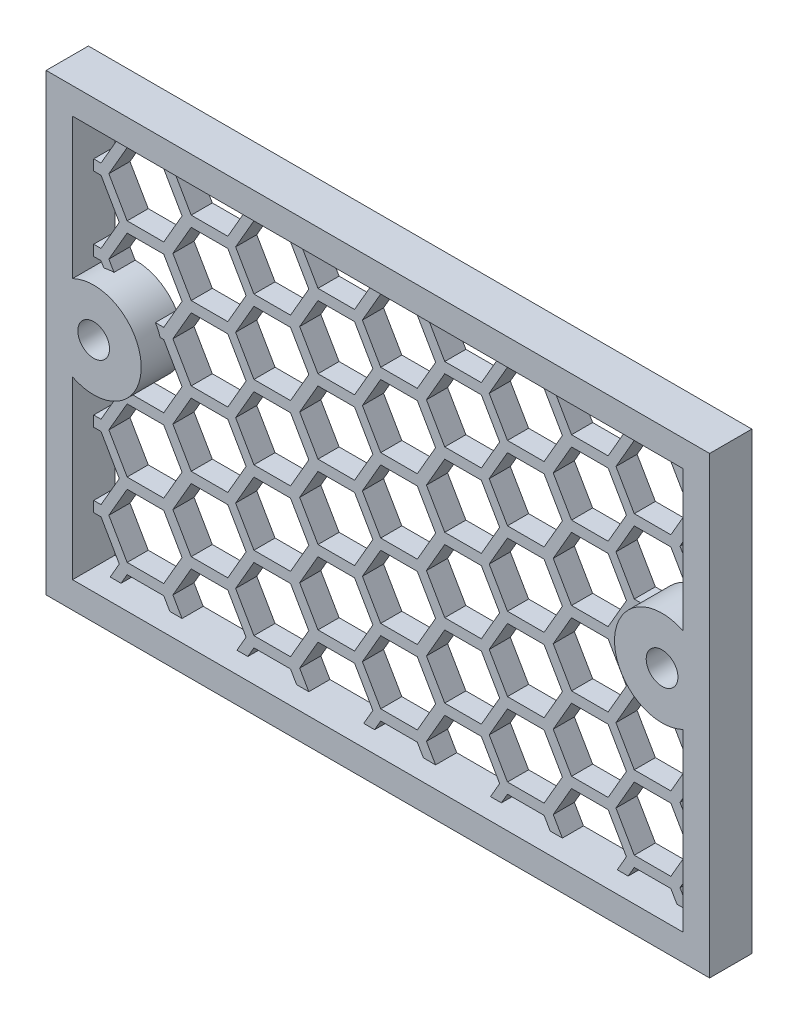
SolidWorks part; units mm, degrees
ref_plane "Plano frontal" through (0, 0, 0) normal (0, 0, 1) x (1, 0, 0)
ref_plane "Plano superior" through (0, 0, 0) normal (0, 1, 0) x (1, 0, 0)
ref_plane "Plano direito" through (0, 0, 0) normal (1, 0, 0) x (0, 0, -1)
sketch "Esboço1" plane through (0, 0, 0) normal (0, 0, 1) x (1, 0, 0)
  line L0 (-45.5019, 12.056) -> (17.2981, 12.056)
  line L1 (-45.5019, 12.056) -> (-45.5019, -30.9425)
  line L2 (-45.5019, -30.9425) -> (17.2981, -30.9425)
  line L3 (17.2981, 12.056) -> (17.2981, -30.9425)
  line L4 (-21.7718, -2.9433) -> (-23.5039, -5.9433)
  line L5 (-23.5039, -5.9433) -> (-21.7718, -8.9433)
  line L6 (-43.0019, 9.556) -> (-43.0019, 5.0567)
  line L7 (-21.7718, -8.9433) -> (-18.3077, -8.9433)
  line L8 (14.7981, 9.556) -> (14.7981, 5.0567)
  line L9 (-18.3077, -8.9433) -> (-16.5757, -5.9433)
  line L10 (-16.5757, -5.9433) -> (-18.3077, -2.9433)
  line L11 (-18.3077, -2.9433) -> (-21.7718, -2.9433)
  line L12 (-10.6378, -9.4433) -> (-12.3699, -6.4433)
  line L13 (-12.3699, -6.4433) -> (-15.834, -6.4433)
  line L14 (-15.834, -6.4433) -> (-17.566, -9.4433)
  line L15 (-17.566, -9.4433) -> (-15.834, -12.4433)
  line L16 (-15.834, -12.4433) -> (-12.3699, -12.4433)
  line L17 (-12.3699, -12.4433) -> (-10.6378, -9.4433)
  line L18 (-15.834, 0.5567) -> (-17.566, -2.4433)
  line L19 (-17.566, -2.4433) -> (-15.834, -5.4433)
  line L20 (-15.834, -5.4433) -> (-12.3699, -5.4433)
  line L21 (-12.3699, -5.4433) -> (-10.6378, -2.4433)
  line L22 (-10.6378, -2.4433) -> (-12.3699, 0.5567)
  line L23 (-12.3699, 0.5567) -> (-15.834, 0.5567)
  line L24 (-15.834, 7.5567) -> (-17.566, 4.5567)
  line L25 (-17.566, 4.5567) -> (-15.834, 1.5567)
  line L26 (-15.834, 1.5567) -> (-12.3699, 1.5567)
  line L27 (-12.3699, 1.5567) -> (-10.6378, 4.5567)
  line L28 (-10.6378, 4.5567) -> (-12.3699, 7.5567)
  line L29 (-12.3699, 7.5567) -> (-15.834, 7.5567)
  line L30 (14.7981, -11.8206) -> (14.7981, -15.9433)
  line L31 (-16.4109, 9.556) -> (-15.834, 8.5567)
  line L32 (-15.834, 8.5567) -> (-12.3699, 8.5567)
  line L33 (-12.3699, 8.5567) -> (-11.793, 9.556)
  line L34 (14.7981, 4.0567) -> (14.2282, 4.0567)
  line L35 (14.7981, -2.9433) -> (14.2282, -2.9433)
  line L36 (-15.834, -13.4433) -> (-17.566, -16.4433)
  line L37 (-17.566, -16.4433) -> (-15.834, -19.4433)
  line L38 (-15.834, -19.4433) -> (-12.3699, -19.4433)
  line L39 (-12.3699, -19.4433) -> (-10.6378, -16.4433)
  line L40 (-10.6378, -16.4433) -> (-12.3699, -13.4433)
  line L41 (-12.3699, -13.4433) -> (-15.834, -13.4433)
  line L42 (-15.834, -20.4433) -> (-17.566, -23.4433)
  line L43 (-17.566, -23.4433) -> (-15.834, -26.4433)
  line L44 (-15.834, -26.4433) -> (-12.3699, -26.4433)
  line L45 (-12.3699, -26.4433) -> (-10.6378, -23.4433)
  line L46 (-10.6378, -23.4433) -> (-12.3699, -20.4433)
  line L47 (-12.3699, -20.4433) -> (-15.834, -20.4433)
  line L48 (-15.834, -27.4433) -> (-16.4109, -28.4425)
  line L49 (-43.0019, 5.0567) -> (-42.3077, 5.0567)
  line L50 (-43.0019, -22.9433) -> (-42.3077, -22.9433)
  line L51 (-43.0019, -2.9433) -> (-43.0019, -3.7583)
  line L52 (-11.793, -28.4425) -> (-12.3699, -27.4433)
  line L53 (-12.3699, -27.4433) -> (-15.834, -27.4433)
  line L54 (-9.7718, -2.9433) -> (-11.5039, -5.9433)
  line L55 (-11.5039, -5.9433) -> (-9.7718, -8.9433)
  line L56 (-9.7718, -8.9433) -> (-6.3077, -8.9433)
  line L57 (-6.3077, -8.9433) -> (-4.5757, -5.9433)
  line L58 (-4.5757, -5.9433) -> (-6.3077, -2.9433)
  line L59 (-6.3077, -2.9433) -> (-9.7718, -2.9433)
  line L60 (-11.5039, 1.0567) -> (-9.7718, -1.9433)
  line L61 (-9.7718, -1.9433) -> (-6.3077, -1.9433)
  line L62 (-6.3077, -1.9433) -> (-4.5757, 1.0567)
  line L63 (-4.5757, 1.0567) -> (-6.3077, 4.0567)
  line L64 (-9.7718, 4.0567) -> (-11.5039, 1.0567)
  line L65 (-6.3077, 4.0567) -> (-9.7718, 4.0567)
  line L66 (-11.5039, 8.0567) -> (-9.7718, 5.0567)
  line L67 (-9.7718, 5.0567) -> (-6.3077, 5.0567)
  line L68 (-6.3077, 5.0567) -> (-4.5757, 8.0567)
  line L69 (-4.5757, 8.0567) -> (-5.4412, 9.556)
  line L70 (-10.6383, 9.556) -> (-11.5039, 8.0567)
  line L71 (-43.0019, -15.9433) -> (-42.3077, -15.9433)
  line L72 (-11.5039, -12.9433) -> (-9.7718, -15.9433)
  line L73 (-9.7718, -15.9433) -> (-6.3077, -15.9433)
  line L74 (-6.3077, -15.9433) -> (-4.5757, -12.9433)
  line L75 (-4.5757, -12.9433) -> (-6.3077, -9.9433)
  line L76 (-9.7718, -9.9433) -> (-11.5039, -12.9433)
  line L77 (-6.3077, -9.9433) -> (-9.7718, -9.9433)
  line L78 (-11.5039, -19.9433) -> (-9.7718, -22.9433)
  line L79 (-9.7718, -22.9433) -> (-6.3077, -22.9433)
  line L80 (-6.3077, -22.9433) -> (-4.5757, -19.9433)
  line L81 (-4.5757, -19.9433) -> (-6.3077, -16.9433)
  line L82 (-9.7718, -16.9433) -> (-11.5039, -19.9433)
  line L83 (-6.3077, -16.9433) -> (-9.7718, -16.9433)
  line L84 (-11.5039, -26.9433) -> (-10.6383, -28.4425)
  line L85 (-43.0019, -11.8206) -> (-43.0019, -15.9433)
  line L86 (-5.4412, -28.4425) -> (-4.5757, -26.9433)
  line L87 (-4.5757, -26.9433) -> (-6.3077, -23.9433)
  line L88 (-9.7718, -23.9433) -> (-11.5039, -26.9433)
  line L89 (-6.3077, -23.9433) -> (-9.7718, -23.9433)
  line L90 (-43.0019, -28.4425) -> (14.7981, -28.4425) construction
  line L91 (-43.0019, 9.556) -> (14.7981, 9.556) construction
  line L92 (-23.5039, 1.0567) -> (-21.7718, -1.9433)
  line L93 (-21.7718, -1.9433) -> (-18.3077, -1.9433)
  line L94 (-18.3077, -1.9433) -> (-16.5757, 1.0567)
  line L95 (-16.5757, 1.0567) -> (-18.3077, 4.0567)
  line L96 (-21.7718, 4.0567) -> (-23.5039, 1.0567)
  line L97 (-18.3077, 4.0567) -> (-21.7718, 4.0567)
  line L98 (-23.5039, 8.0567) -> (-21.7718, 5.0567)
  line L99 (-21.7718, 5.0567) -> (-18.3077, 5.0567)
  line L100 (-18.3077, 5.0567) -> (-16.5757, 8.0567)
  line L101 (-16.5757, 8.0567) -> (-17.4412, 9.556)
  line L102 (-22.6383, 9.556) -> (-23.5039, 8.0567)
  line L103 (14.7981, 9.556) -> (14.7981, -28.4425) construction
  line L104 (-23.5039, -12.9433) -> (-21.7718, -15.9433)
  line L105 (-21.7718, -15.9433) -> (-18.3077, -15.9433)
  line L106 (-18.3077, -15.9433) -> (-16.5757, -12.9433)
  line L107 (-16.5757, -12.9433) -> (-18.3077, -9.9433)
  line L108 (-21.7718, -9.9433) -> (-23.5039, -12.9433)
  line L109 (-18.3077, -9.9433) -> (-21.7718, -9.9433)
  line L110 (-23.5039, -19.9433) -> (-21.7718, -22.9433)
  line L111 (-21.7718, -22.9433) -> (-18.3077, -22.9433)
  line L112 (-18.3077, -22.9433) -> (-16.5757, -19.9433)
  line L113 (-16.5757, -19.9433) -> (-18.3077, -16.9433)
  line L114 (-21.7718, -16.9433) -> (-23.5039, -19.9433)
  line L115 (-18.3077, -16.9433) -> (-21.7718, -16.9433)
  line L116 (-23.5039, -26.9433) -> (-22.6383, -28.4425)
  line L117 (-43.0019, -1.9433) -> (-42.3077, -1.9433)
  line L118 (-17.4412, -28.4425) -> (-16.5757, -26.9433)
  line L119 (-16.5757, -26.9433) -> (-18.3077, -23.9433)
  line L120 (-21.7718, -23.9433) -> (-23.5039, -26.9433)
  line L121 (-18.3077, -23.9433) -> (-21.7718, -23.9433)
  line L122 (-33.7718, -2.9433) -> (-35.5039, -5.9433)
  line L123 (-35.5039, -5.9433) -> (-33.7718, -8.9433)
  line L124 (-33.7718, -8.9433) -> (-30.3077, -8.9433)
  line L125 (-30.3077, -8.9433) -> (-28.5757, -5.9433)
  line L126 (-28.5757, -5.9433) -> (-30.3077, -2.9433)
  line L127 (-30.3077, -2.9433) -> (-33.7718, -2.9433)
  line L128 (-35.5039, 1.0567) -> (-33.7718, -1.9433)
  line L129 (-33.7718, -1.9433) -> (-30.3077, -1.9433)
  line L130 (-30.3077, -1.9433) -> (-28.5757, 1.0567)
  line L131 (-28.5757, 1.0567) -> (-30.3077, 4.0567)
  line L132 (-33.7718, 4.0567) -> (-35.5039, 1.0567)
  line L133 (-30.3077, 4.0567) -> (-33.7718, 4.0567)
  line L134 (-35.5039, 8.0567) -> (-33.7718, 5.0567)
  line L135 (-33.7718, 5.0567) -> (-30.3077, 5.0567)
  line L136 (-30.3077, 5.0567) -> (-28.5757, 8.0567)
  line L137 (-28.5757, 8.0567) -> (-29.4412, 9.556)
  line L138 (-34.6383, 9.556) -> (-35.5039, 8.0567)
  line L139 (8.5042, -6.4433) -> (8.166, -6.4433)
  line L140 (-35.5039, -12.9433) -> (-33.7718, -15.9433)
  line L141 (-33.7718, -15.9433) -> (-30.3077, -15.9433)
  line L142 (-30.3077, -15.9433) -> (-28.5757, -12.9433)
  line L143 (-28.5757, -12.9433) -> (-30.3077, -9.9433)
  line L144 (-33.7718, -9.9433) -> (-35.5039, -12.9433)
  line L145 (-30.3077, -9.9433) -> (-33.7718, -9.9433)
  line L146 (-35.5039, -19.9433) -> (-33.7718, -22.9433)
  line L147 (-33.7718, -22.9433) -> (-30.3077, -22.9433)
  line L148 (-30.3077, -22.9433) -> (-28.5757, -19.9433)
  line L149 (-28.5757, -19.9433) -> (-30.3077, -16.9433)
  line L150 (-33.7718, -16.9433) -> (-35.5039, -19.9433)
  line L151 (-30.3077, -16.9433) -> (-33.7718, -16.9433)
  line L152 (-35.5039, -26.9433) -> (-34.6383, -28.4425)
  line L153 (-43.0019, 9.556) -> (-43.0019, -28.4425) construction
  line L154 (-29.4412, -28.4425) -> (-28.5757, -26.9433)
  line L155 (-28.5757, -26.9433) -> (-30.3077, -23.9433)
  line L156 (-33.7718, -23.9433) -> (-35.5039, -26.9433)
  line L157 (-30.3077, -23.9433) -> (-33.7718, -23.9433)
  line L158 (14.7981, -16.9433) -> (14.2282, -16.9433)
  line L159 (14.7981, -23.9433) -> (14.2282, -23.9433)
  line L160 (-39.9894, -12.1741) -> (-39.834, -12.4433)
  line L161 (-43.0019, -16.9433) -> (-43.0019, -22.9433)
  line L162 (-42.038, -3.4104) -> (-42.3077, -2.9433)
  line L163 (-42.3077, -2.9433) -> (-43.0019, -2.9433)
  line L164 (-43.0019, -23.9433) -> (-43.0019, -28.4425)
  line L165 (-40.4109, -28.4425) -> (-35.793, -28.4425)
  line L166 (-42.3077, -1.9433) -> (-40.5757, 1.0567)
  line L167 (-40.5757, 1.0567) -> (-42.3077, 4.0567)
  line L168 (-34.6383, -28.4425) -> (-29.4412, -28.4425)
  line L169 (-42.3077, 4.0567) -> (-43.0019, 4.0567)
  line L170 (-28.4109, -28.4425) -> (-23.793, -28.4425)
  line L171 (-22.6383, -28.4425) -> (-17.4412, -28.4425)
  line L172 (-42.3077, 5.0567) -> (-40.5757, 8.0567)
  line L173 (-40.5757, 8.0567) -> (-41.4412, 9.556)
  line L174 (-16.4109, -28.4425) -> (-11.793, -28.4425)
  line L175 (-10.6383, -28.4425) -> (-5.4412, -28.4425)
  line L176 (-4.4109, -28.4425) -> (0.207, -28.4425)
  line L177 (1.3617, -28.4425) -> (6.5588, -28.4425)
  line L178 (-42.3077, -15.9433) -> (-40.5757, -12.9433)
  line L179 (-40.5757, -12.9433) -> (-40.9533, -12.2892)
  line L180 (7.5891, -28.4425) -> (12.207, -28.4425)
  line L181 (13.3617, -28.4425) -> (14.7981, -28.4425)
  line L182 (14.7981, -23.9433) -> (14.7981, -28.4425)
  line L183 (14.7981, -16.9433) -> (14.7981, -22.9433)
  line L184 (-42.3077, -22.9433) -> (-40.5757, -19.9433)
  line L185 (-40.5757, -19.9433) -> (-42.3077, -16.9433)
  line L186 (14.7981, -2.9433) -> (14.7981, -3.7583)
  line L187 (-42.3077, -16.9433) -> (-43.0019, -16.9433)
  line L188 (14.7981, 4.0567) -> (14.7981, -1.9433)
  line L189 (13.3617, 9.556) -> (14.7981, 9.556)
  line L190 (-41.4412, -28.4425) -> (-40.5757, -26.9433)
  line L191 (-40.5757, -26.9433) -> (-42.3077, -23.9433)
  line L192 (7.5891, 9.556) -> (12.207, 9.556)
  line L193 (-42.3077, -23.9433) -> (-43.0019, -23.9433)
  line L194 (2.2282, -2.9433) -> (0.4961, -5.9433)
  line L195 (0.4961, -5.9433) -> (2.2282, -8.9433)
  line L196 (2.2282, -8.9433) -> (5.6923, -8.9433)
  line L197 (5.6923, -8.9433) -> (7.4243, -5.9433)
  line L198 (7.4243, -5.9433) -> (5.6923, -2.9433)
  line L199 (5.6923, -2.9433) -> (2.2282, -2.9433)
  line L200 (0.4961, 1.0567) -> (2.2282, -1.9433)
  line L201 (2.2282, -1.9433) -> (5.6923, -1.9433)
  line L202 (5.6923, -1.9433) -> (7.4243, 1.0567)
  line L203 (7.4243, 1.0567) -> (5.6923, 4.0567)
  line L204 (2.2282, 4.0567) -> (0.4961, 1.0567)
  line L205 (5.6923, 4.0567) -> (2.2282, 4.0567)
  line L206 (0.4961, 8.0567) -> (2.2282, 5.0567)
  line L207 (2.2282, 5.0567) -> (5.6923, 5.0567)
  line L208 (5.6923, 5.0567) -> (7.4243, 8.0567)
  line L209 (7.4243, 8.0567) -> (6.5588, 9.556)
  line L210 (1.3617, 9.556) -> (0.4961, 8.0567)
  line L211 (1.3617, 9.556) -> (6.5588, 9.556)
  line L212 (0.4961, -12.9433) -> (2.2282, -15.9433)
  line L213 (2.2282, -15.9433) -> (5.6923, -15.9433)
  line L214 (5.6923, -15.9433) -> (7.4243, -12.9433)
  line L215 (7.4243, -12.9433) -> (5.6923, -9.9433)
  line L216 (2.2282, -9.9433) -> (0.4961, -12.9433)
  line L217 (5.6923, -9.9433) -> (2.2282, -9.9433)
  line L218 (0.4961, -19.9433) -> (2.2282, -22.9433)
  line L219 (2.2282, -22.9433) -> (5.6923, -22.9433)
  line L220 (5.6923, -22.9433) -> (7.4243, -19.9433)
  line L221 (7.4243, -19.9433) -> (5.6923, -16.9433)
  line L222 (2.2282, -16.9433) -> (0.4961, -19.9433)
  line L223 (5.6923, -16.9433) -> (2.2282, -16.9433)
  line L224 (0.4961, -26.9433) -> (1.3617, -28.4425)
  line L225 (-4.4109, 9.556) -> (0.207, 9.556)
  line L226 (6.5588, -28.4425) -> (7.4243, -26.9433)
  line L227 (7.4243, -26.9433) -> (5.6923, -23.9433)
  line L228 (2.2282, -23.9433) -> (0.4961, -26.9433)
  line L229 (5.6923, -23.9433) -> (2.2282, -23.9433)
  line L230 (14.2282, -2.9433) -> (13.9428, -3.4375)
  line L231 (-10.6383, 9.556) -> (-5.4412, 9.556)
  line L232 (-16.4109, 9.556) -> (-11.793, 9.556)
  line L233 (-22.6383, 9.556) -> (-17.4412, 9.556)
  line L234 (-28.4109, 9.556) -> (-23.793, 9.556)
  line L235 (-34.6383, 9.556) -> (-29.4412, 9.556)
  line L236 (12.4961, 1.0567) -> (14.2282, -1.9433)
  line L237 (14.2282, -1.9433) -> (14.7981, -1.9433)
  line L238 (-40.4109, 9.556) -> (-35.793, 9.556)
  line L239 (-43.0019, 4.0567) -> (-43.0019, -1.9433)
  line L240 (14.2282, 4.0567) -> (12.4961, 1.0567)
  line L242 (12.4961, 8.0567) -> (14.2282, 5.0567)
  line L243 (14.2282, 5.0567) -> (14.7981, 5.0567)
  line L246 (13.3617, 9.556) -> (12.4961, 8.0567)
  line L248 (12.4961, -12.9433) -> (14.2282, -15.9433)
  line L249 (14.2282, -15.9433) -> (14.7981, -15.9433)
  line L252 (12.874, -12.2888) -> (12.4961, -12.9433)
  line L254 (12.4961, -19.9433) -> (14.2282, -22.9433)
  line L255 (14.2282, -22.9433) -> (14.7981, -22.9433)
  line L258 (14.2282, -16.9433) -> (12.4961, -19.9433)
  line L260 (12.4961, -26.9433) -> (13.3617, -28.4425)
  line L264 (14.2282, -23.9433) -> (12.4961, -26.9433)
  line L266 (1.3622, -9.4433) -> (-0.3699, -6.4433)
  line L267 (-0.3699, -6.4433) -> (-3.834, -6.4433)
  line L268 (-3.834, -6.4433) -> (-5.566, -9.4433)
  line L269 (-5.566, -9.4433) -> (-3.834, -12.4433)
  line L270 (-3.834, -12.4433) -> (-0.3699, -12.4433)
  line L271 (-0.3699, -12.4433) -> (1.3622, -9.4433)
  line L272 (-3.834, 0.5567) -> (-5.566, -2.4433)
  line L273 (-5.566, -2.4433) -> (-3.834, -5.4433)
  line L274 (-3.834, -5.4433) -> (-0.3699, -5.4433)
  line L275 (-0.3699, -5.4433) -> (1.3622, -2.4433)
  line L276 (1.3622, -2.4433) -> (-0.3699, 0.5567)
  line L277 (-0.3699, 0.5567) -> (-3.834, 0.5567)
  line L278 (-3.834, 7.5567) -> (-5.566, 4.5567)
  line L279 (-5.566, 4.5567) -> (-3.834, 1.5567)
  line L280 (-3.834, 1.5567) -> (-0.3699, 1.5567)
  line L281 (-0.3699, 1.5567) -> (1.3622, 4.5567)
  line L282 (1.3622, 4.5567) -> (-0.3699, 7.5567)
  line L283 (-0.3699, 7.5567) -> (-3.834, 7.5567)
  line L284 (-4.4109, 9.556) -> (-3.834, 8.5567)
  line L285 (-3.834, 8.5567) -> (-0.3699, 8.5567)
  line L286 (-0.3699, 8.5567) -> (0.207, 9.556)
  line L287 (-3.834, -13.4433) -> (-5.566, -16.4433)
  line L288 (-5.566, -16.4433) -> (-3.834, -19.4433)
  line L289 (-3.834, -19.4433) -> (-0.3699, -19.4433)
  line L290 (-0.3699, -19.4433) -> (1.3622, -16.4433)
  line L291 (1.3622, -16.4433) -> (-0.3699, -13.4433)
  line L292 (-0.3699, -13.4433) -> (-3.834, -13.4433)
  line L293 (-3.834, -20.4433) -> (-5.566, -23.4433)
  line L294 (-5.566, -23.4433) -> (-3.834, -26.4433)
  line L295 (-3.834, -26.4433) -> (-0.3699, -26.4433)
  line L296 (-0.3699, -26.4433) -> (1.3622, -23.4433)
  line L297 (1.3622, -23.4433) -> (-0.3699, -20.4433)
  line L298 (-0.3699, -20.4433) -> (-3.834, -20.4433)
  line L299 (-3.834, -27.4433) -> (-4.4109, -28.4425)
  line L300 (0.207, -28.4425) -> (-0.3699, -27.4433)
  line L301 (-0.3699, -27.4433) -> (-3.834, -27.4433)
  line L304 (8.166, -6.4433) -> (6.434, -9.4433)
  line L305 (6.434, -9.4433) -> (8.166, -12.4433)
  line L306 (8.166, -12.4433) -> (11.6301, -12.4433)
  line L307 (11.6301, -12.4433) -> (11.7855, -12.1741)
  line L308 (8.166, 0.5567) -> (6.434, -2.4433)
  line L309 (6.434, -2.4433) -> (8.166, -5.4433)
  line L310 (8.166, -5.4433) -> (8.9581, -5.4433)
  line L311 (12.8732, -3.2901) -> (13.3622, -2.4433)
  line L312 (13.3622, -2.4433) -> (11.6301, 0.5567)
  line L313 (11.6301, 0.5567) -> (8.166, 0.5567)
  line L314 (8.166, 7.5567) -> (6.434, 4.5567)
  line L315 (6.434, 4.5567) -> (8.166, 1.5567)
  line L316 (8.166, 1.5567) -> (11.6301, 1.5567)
  line L317 (11.6301, 1.5567) -> (13.3622, 4.5567)
  line L318 (13.3622, 4.5567) -> (11.6301, 7.5567)
  line L319 (11.6301, 7.5567) -> (8.166, 7.5567)
  line L320 (7.5891, 9.556) -> (8.166, 8.5567)
  line L321 (8.166, 8.5567) -> (11.6301, 8.5567)
  line L322 (11.6301, 8.5567) -> (12.207, 9.556)
  line L323 (8.166, -13.4433) -> (6.434, -16.4433)
  line L324 (6.434, -16.4433) -> (8.166, -19.4433)
  line L325 (8.166, -19.4433) -> (11.6301, -19.4433)
  line L326 (11.6301, -19.4433) -> (13.3622, -16.4433)
  line L327 (13.3622, -16.4433) -> (11.6301, -13.4433)
  line L328 (11.6301, -13.4433) -> (8.166, -13.4433)
  line L329 (8.166, -20.4433) -> (6.434, -23.4433)
  line L330 (6.434, -23.4433) -> (8.166, -26.4433)
  line L331 (8.166, -26.4433) -> (11.6301, -26.4433)
  line L332 (11.6301, -26.4433) -> (13.3622, -23.4433)
  line L333 (13.3622, -23.4433) -> (11.6301, -20.4433)
  line L334 (11.6301, -20.4433) -> (8.166, -20.4433)
  line L335 (8.166, -27.4433) -> (7.5891, -28.4425)
  line L336 (12.207, -28.4425) -> (11.6301, -27.4433)
  line L337 (11.6301, -27.4433) -> (8.166, -27.4433)
  line L338 (-22.6378, -9.4433) -> (-24.3699, -6.4433)
  line L339 (-24.3699, -6.4433) -> (-27.834, -6.4433)
  line L340 (-27.834, -6.4433) -> (-29.566, -9.4433)
  line L341 (-29.566, -9.4433) -> (-27.834, -12.4433)
  line L342 (-27.834, -12.4433) -> (-24.3699, -12.4433)
  line L343 (-24.3699, -12.4433) -> (-22.6378, -9.4433)
  line L344 (-27.834, 0.5567) -> (-29.566, -2.4433)
  line L345 (-29.566, -2.4433) -> (-27.834, -5.4433)
  line L346 (-27.834, -5.4433) -> (-24.3699, -5.4433)
  line L347 (-24.3699, -5.4433) -> (-22.6378, -2.4433)
  line L348 (-22.6378, -2.4433) -> (-24.3699, 0.5567)
  line L349 (-24.3699, 0.5567) -> (-27.834, 0.5567)
  line L350 (-27.834, 7.5567) -> (-29.566, 4.5567)
  line L351 (-29.566, 4.5567) -> (-27.834, 1.5567)
  line L352 (-27.834, 1.5567) -> (-24.3699, 1.5567)
  line L353 (-24.3699, 1.5567) -> (-22.6378, 4.5567)
  line L354 (-22.6378, 4.5567) -> (-24.3699, 7.5567)
  line L355 (-24.3699, 7.5567) -> (-27.834, 7.5567)
  line L356 (-28.4109, 9.556) -> (-27.834, 8.5567)
  line L357 (-27.834, 8.5567) -> (-24.3699, 8.5567)
  line L358 (-24.3699, 8.5567) -> (-23.793, 9.556)
  line L359 (-27.834, -13.4433) -> (-29.566, -16.4433)
  line L360 (-29.566, -16.4433) -> (-27.834, -19.4433)
  line L361 (-27.834, -19.4433) -> (-24.3699, -19.4433)
  line L362 (-24.3699, -19.4433) -> (-22.6378, -16.4433)
  line L363 (-22.6378, -16.4433) -> (-24.3699, -13.4433)
  line L364 (-24.3699, -13.4433) -> (-27.834, -13.4433)
  line L365 (-27.834, -20.4433) -> (-29.566, -23.4433)
  line L366 (-29.566, -23.4433) -> (-27.834, -26.4433)
  line L367 (-27.834, -26.4433) -> (-24.3699, -26.4433)
  line L368 (-24.3699, -26.4433) -> (-22.6378, -23.4433)
  line L369 (-22.6378, -23.4433) -> (-24.3699, -20.4433)
  line L370 (-24.3699, -20.4433) -> (-27.834, -20.4433)
  line L371 (-27.834, -27.4433) -> (-28.4109, -28.4425)
  line L372 (-23.793, -28.4425) -> (-24.3699, -27.4433)
  line L373 (-24.3699, -27.4433) -> (-27.834, -27.4433)
  line L374 (-34.6378, -9.4433) -> (-36.3699, -6.4433)
  line L375 (-36.3699, -6.4433) -> (-36.708, -6.4433)
  line L378 (-39.834, -12.4433) -> (-36.3699, -12.4433)
  line L379 (-36.3699, -12.4433) -> (-34.6378, -9.4433)
  line L380 (-39.834, 0.5567) -> (-41.566, -2.4433)
  line L381 (-41.566, -2.4433) -> (-41.0771, -3.2901)
  line L382 (-37.162, -5.4433) -> (-36.3699, -5.4433)
  line L383 (-36.3699, -5.4433) -> (-34.6378, -2.4433)
  line L384 (-34.6378, -2.4433) -> (-36.3699, 0.5567)
  line L385 (-36.3699, 0.5567) -> (-39.834, 0.5567)
  line L386 (-39.834, 7.5567) -> (-41.566, 4.5567)
  line L387 (-41.566, 4.5567) -> (-39.834, 1.5567)
  line L388 (-39.834, 1.5567) -> (-36.3699, 1.5567)
  line L389 (-36.3699, 1.5567) -> (-34.6378, 4.5567)
  line L390 (-34.6378, 4.5567) -> (-36.3699, 7.5567)
  line L391 (-36.3699, 7.5567) -> (-39.834, 7.5567)
  line L392 (-40.4109, 9.556) -> (-39.834, 8.5567)
  line L393 (-39.834, 8.5567) -> (-36.3699, 8.5567)
  line L394 (-36.3699, 8.5567) -> (-35.793, 9.556)
  line L395 (-39.834, -13.4433) -> (-41.566, -16.4433)
  line L396 (-41.566, -16.4433) -> (-39.834, -19.4433)
  line L397 (-39.834, -19.4433) -> (-36.3699, -19.4433)
  line L398 (-36.3699, -19.4433) -> (-34.6378, -16.4433)
  line L399 (-34.6378, -16.4433) -> (-36.3699, -13.4433)
  line L400 (-36.3699, -13.4433) -> (-39.834, -13.4433)
  line L401 (-39.834, -20.4433) -> (-41.566, -23.4433)
  line L402 (-41.566, -23.4433) -> (-39.834, -26.4433)
  line L403 (-39.834, -26.4433) -> (-36.3699, -26.4433)
  line L404 (-36.3699, -26.4433) -> (-34.6378, -23.4433)
  line L405 (-34.6378, -23.4433) -> (-36.3699, -20.4433)
  line L406 (-36.3699, -20.4433) -> (-39.834, -20.4433)
  line L407 (-39.834, -27.4433) -> (-40.4109, -28.4425)
  line L408 (-35.793, -28.4425) -> (-36.3699, -27.4433)
  line L409 (-36.3699, -27.4433) -> (-39.834, -27.4433)
  line L410 (-43.0019, 9.556) -> (-41.4412, 9.556)
  line L411 (-43.0019, -28.4425) -> (-41.4412, -28.4425)
  line L412 (-45.7718, -2.9433) -> (-47.5039, -5.9433) [skipped]
  line L413 (-47.5039, -5.9433) -> (-45.7718, -8.9433) [skipped]
  line L414 (-47.5039, 1.0567) -> (-45.7718, -1.9433) [skipped]
  line L415 (-45.7718, 4.0567) -> (-47.5039, 1.0567) [skipped]
  line L416 (-47.5039, 8.0567) -> (-45.7718, 5.0567) [skipped]
  line L417 (-45.7718, 11.0567) -> (-47.5039, 8.0567) [skipped]
  line L418 (-47.5039, -12.9433) -> (-45.7718, -15.9433) [skipped]
  line L419 (-45.7718, -9.9433) -> (-47.5039, -12.9433) [skipped]
  line L420 (-47.5039, -19.9433) -> (-45.7718, -22.9433) [skipped]
  line L421 (-45.7718, -16.9433) -> (-47.5039, -19.9433) [skipped]
  line L422 (-47.5039, -26.9433) -> (-45.7718, -29.9433) [skipped]
  line L423 (-45.7718, -23.9433) -> (-47.5039, -26.9433) [skipped]
  line L424 (17.6923, -8.9433) -> (19.4243, -5.9433) [skipped]
  line L425 (19.4243, -5.9433) -> (17.6923, -2.9433) [skipped]
  line L426 (17.6923, -1.9433) -> (19.4243, 1.0567) [skipped]
  line L427 (19.4243, 1.0567) -> (17.6923, 4.0567) [skipped]
  line L428 (17.6923, 5.0567) -> (19.4243, 8.0567) [skipped]
  line L429 (19.4243, 8.0567) -> (17.6923, 11.0567) [skipped]
  line L430 (17.6923, -15.9433) -> (19.4243, -12.9433) [skipped]
  line L431 (19.4243, -12.9433) -> (17.6923, -9.9433) [skipped]
  line L432 (17.6923, -22.9433) -> (19.4243, -19.9433) [skipped]
  line L433 (19.4243, -19.9433) -> (17.6923, -16.9433) [skipped]
  line L434 (17.6923, -29.9433) -> (19.4243, -26.9433) [skipped]
  line L435 (19.4243, -26.9433) -> (17.6923, -23.9433) [skipped]
  line L439 (-15.834, 14.5567) -> (-17.2778, 12.056) [skipped]
  line L440 (-10.9261, 12.056) -> (-12.3699, 14.5567) [skipped]
  line L441 (-12.3699, 14.5567) -> (-15.834, 14.5567) [skipped]
  line L442 (-6.3077, 11.0567) -> (-9.7718, 11.0567) [skipped]
  line L443 (17.6923, 4.0567) -> (17.2981, 4.0567) [skipped]
  line L444 (17.6923, -2.9433) -> (17.2981, -2.9433) [skipped]
  line L445 (17.6923, -9.9433) -> (17.2981, -9.9433) [skipped]
  line L446 (11.6301, -6.4433) -> (9.8981, -6.4433) [skipped]
  line L447 (14.2282, -8.9433) -> (14.7981, -8.9433) [skipped]
  line L448 (12.4961, -5.9433) -> (12.698, -6.2928) [skipped]
  line L449 (13.3622, -9.4433) -> (13.2357, -9.2242) [skipped]
  line L450 (17.6923, -16.9433) -> (17.2981, -16.9433) [skipped]
  line L451 (17.6923, -23.9433) -> (17.2981, -23.9433) [skipped]
  line L454 (-9.7718, -29.9433) -> (-6.3077, -29.9433) [skipped]
  line L455 (-17.2778, -30.9425) -> (-15.834, -33.4433) [skipped]
  line L456 (-12.3699, -33.4433) -> (-10.9261, -30.9425) [skipped]
  line L457 (-15.834, -33.4433) -> (-12.3699, -33.4433) [skipped]
  line L458 (-45.7718, -15.9433) -> (-45.5019, -15.9433) [skipped]
  line L459 (-45.7718, -22.9433) -> (-45.5019, -22.9433) [skipped]
  line L460 (-45.7718, -8.9433) -> (-45.5019, -8.9433) [skipped]
  line L461 (-45.7718, -1.9433) -> (-45.5019, -1.9433) [skipped]
  line L462 (-45.7718, 5.0567) -> (-45.5019, 5.0567) [skipped]
  line L463 (-42.3077, -9.9433) -> (-43.0019, -9.9433) [skipped]
  line L464 (-41.566, -9.4433) -> (-40.7, -10.9433) [skipped]
  line L465 (-42.1786, -8.7197) -> (-40.7847, -6.3053) [skipped]
  line L466 (-39.9782, -6.6931) -> (-40.7, -7.9433) [skipped]
  circle A0 centre (-41.0019, -7.7895) radius 1.5
  circle A1 centre (12.7981, -7.7895) radius 1.5
  arc A2 (-43.0019, -11.8206) -> (-40.9533, -12.2892) centre (-41.0019, -7.7895) ccw
  arc A3 (14.7981, -3.7583) -> (13.9428, -3.4375) centre (12.7981, -7.7895) ccw
  circle A4 centre (-14.1019, -9.4433) radius 3 construction
  circle A5 centre (-2.1019, -9.4433) radius 3 construction
  arc A6 (-42.038, -3.4104) -> (-43.0019, -3.7583) centre (-41.0019, -7.7895) ccw
  circle A7 centre (-26.1019, -9.4433) radius 3 construction
  arc A8 (-39.5744, -12.057) -> (-36.6021, -6.8451) centre (-38.1019, -9.4433) ccw construction
  arc A9 (8.3983, -6.8451) -> (11.3705, -12.057) centre (9.8981, -9.4433) ccw construction
  arc A10 (12.894, -9.2864) -> (12.4961, -7.9433) centre (9.8981, -9.4433) ccw construction
  arc A11 (-37.162, -5.4433) -> (-41.0771, -3.2901) centre (-41.0019, -7.7895) ccw
  arc A12 (-39.9894, -12.1741) -> (-36.708, -6.4433) centre (-41.0019, -7.7895) ccw
  arc A13 (12.874, -12.2888) -> (14.7981, -11.8206) centre (12.7981, -7.7895) ccw
  arc A14 (8.5042, -6.4433) -> (11.7855, -12.1741) centre (12.7981, -7.7895) ccw
  arc A15 (12.8732, -3.2901) -> (8.9581, -5.4433) centre (12.7981, -7.7895) ccw
  point P0 (-41.0019, -7.7895)
  point P1 (12.7981, -7.7895)
  point P2 (-45.5019, 12.056)
  point P3 (17.2981, 12.056)
  point P4 (17.2981, -30.9425)
  point P5 (-45.5019, -30.9425)
  point P14 (-14.1019, -9.4433)
  point P282 (-2.1019, -9.4433)
  point P323 (9.8981, -9.4433)
  point P364 (-26.1019, -9.4433)
  point P405 (-38.1019, -9.4433)
  dimension "D1" = 2.5
  dimension "D2" = 4
  dimension "D3" = 4
  dimension "D4" = 2
  dimension "D5" = 3
  dimension "D6" = 4
extrude "Ressalto-extrusão1" add sketch "Esboço1" along normal blind 2
sketch "Esboço2" plane through (0, 0, 2) normal (0, 0, 1) x (1, 0, 0)
  line L0 (-43.0019, -3.7583) -> (-43.0019, 9.556)
  line L1 (-45.5019, 12.056) -> (17.2981, 12.056)
  line L2 (-45.5019, 12.056) -> (-45.5019, -30.9425)
  line L3 (-45.5019, -30.9425) -> (17.2981, -30.9425)
  line L4 (17.2981, 12.056) -> (17.2981, -30.9425)
  line L5 (14.7981, -28.4425) -> (-43.0019, -28.4425)
  line L6 (14.7981, -28.4425) -> (14.7981, -11.8206)
  line L7 (14.7981, 9.556) -> (-43.0019, 9.556)
  line L8 (-43.0019, -28.4425) -> (-43.0019, -11.8206)
  line L9 (14.7981, -3.7583) -> (14.7981, 9.556)
  circle A0 centre (-41.0019, -7.7895) radius 1.5
  arc A1 (-43.0019, -11.8206) -> (-43.0019, -3.7583) centre (-41.0019, -7.7895) ccw
  circle A2 centre (12.7981, -7.7895) radius 1.5
  arc A3 (14.7981, -3.7583) -> (14.7981, -11.8206) centre (12.7981, -7.7895) ccw
extrude "Ressalto-extrusão2" add sketch "Esboço2" along normal blind 2
